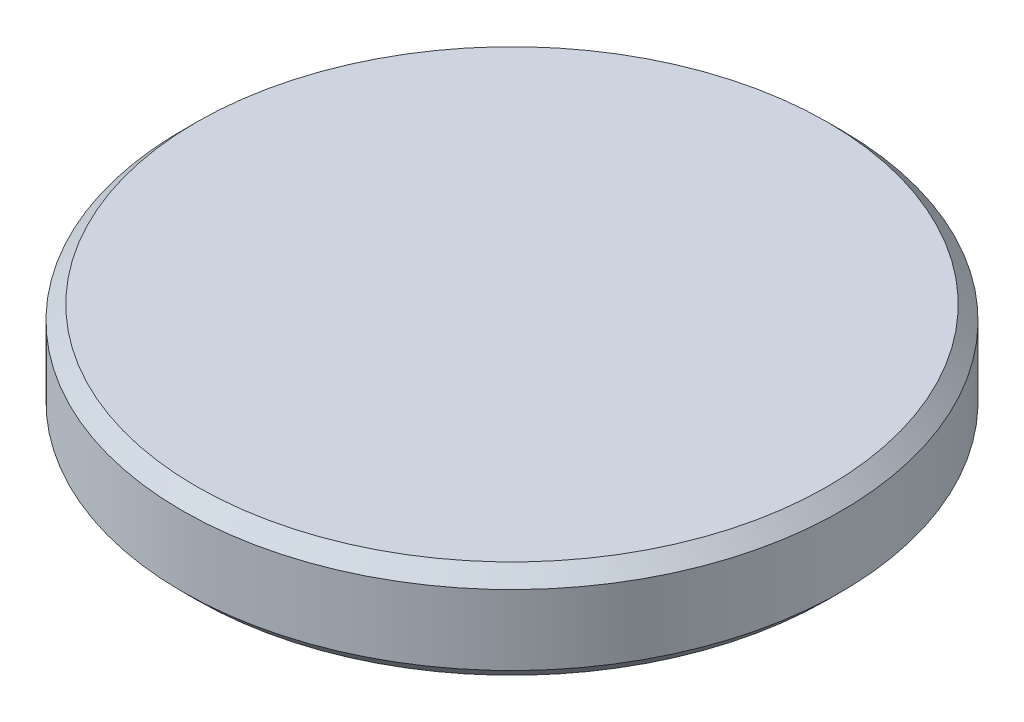
SolidWorks part; units mm, degrees
material "Простая углеродистая сталь"
ref_plane "Front" through (0, 0, 0) normal (0, 0, 1) x (1, 0, 0)
ref_plane "Top" through (0, 0, 0) normal (0, 1, 0) x (1, 0, 0)
ref_plane "Right" through (0, 0, 0) normal (1, 0, 0) x (0, 0, -1)
sketch "Эскиз1" plane through (0, 0, 0) normal (0, 1, 0) x (1, 0, 0)
  circle A0 centre (0, 0) radius 3.525
  dimension "D1" = 7.05
extrude "База" add sketch "Эскиз1" along normal blind 1.05
chamfer "Фаска1" distance 0.15 angle 45 2 edges at (0, 0, 3.525) (0, 1.05, 3.525)
